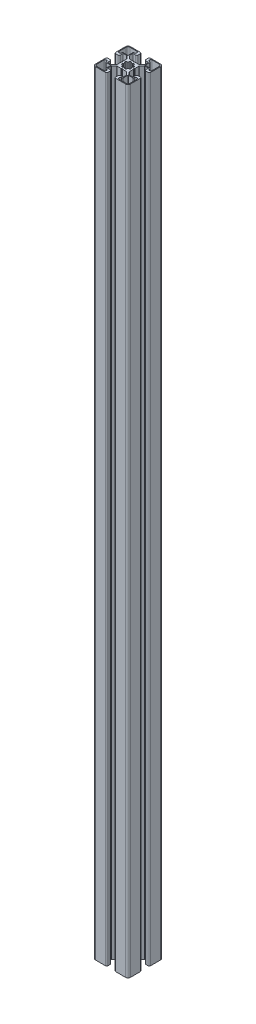
SolidWorks part; units mm, degrees
material "Commercially Pure CP-Ti UNS R50400 (SS)"
ref_plane "Front Plane" through (0, 0, 0) normal (0, 0, 1) x (1, 0, 0)
ref_plane "Top Plane" through (0, 0, 0) normal (0, 1, 0) x (1, 0, 0)
ref_plane "Right Plane" through (0, 0, 0) normal (1, 0, 0) x (0, 0, -1)
sketch "Sketch1" plane through (0, 0, 0) normal (0, 1, 0) x (1, 0, 0)
  line L0 (13.9698, 21.2743) -> (13.5298, 21.2743)
  line L1 (12.0298, 22.7743) -> (12.0298, 23.2743)
  line L2 (13.5298, 24.7743) -> (23.1398, 24.7743)
  line L3 (25.4198, 22.4943) -> (25.4198, 12.8843)
  line L4 (23.9198, 11.3843) -> (23.4198, 11.3843)
  line L5 (21.9198, 12.8843) -> (21.9198, 13.3243)
  line L6 (20.9198, 14.3243) -> (15.3498, 14.3243)
  line L7 (14.9698, 14.7043) -> (14.9698, 20.2743)
  line L8 (21.9589, -6.6897) -> (21.9589, -6.2497)
  line L9 (23.4589, -4.7497) -> (23.9589, -4.7497)
  line L10 (25.4589, -6.2497) -> (25.4589, -15.8597)
  line L11 (23.1789, -18.1397) -> (13.5689, -18.1397)
  line L12 (12.0689, -16.6397) -> (12.0689, -16.1397)
  line L13 (13.5689, -14.6397) -> (14.0089, -14.6397)
  line L14 (15.0089, -13.6397) -> (15.0089, -8.0697)
  line L15 (15.3889, -7.6897) -> (20.9589, -7.6897)
  line L16 (-6.0052, -14.6787) -> (-5.5652, -14.6787)
  line L17 (-4.0652, -16.1787) -> (-4.0652, -16.6787)
  line L18 (-5.5652, -18.1787) -> (-15.1752, -18.1787)
  line L19 (-17.4552, -15.8987) -> (-17.4552, -6.2887)
  line L20 (-15.9552, -4.7887) -> (-15.4552, -4.7887)
  line L21 (-13.9552, -6.2887) -> (-13.9552, -6.7287)
  line L22 (-12.9552, -7.7287) -> (-7.3852, -7.7287)
  line L23 (-7.0052, -8.1087) -> (-7.0052, -13.6787)
  line L24 (1.8289, -2.4886) -> (1.4132, -2.3164)
  line L25 (-1.632, 0.7289) -> (-1.8042, 1.1447)
  line L26 (-1.804, 5.4512) -> (-1.6318, 5.867)
  line L27 (1.4134, 8.9121) -> (1.8292, 9.0843)
  line L28 (6.1358, 9.0842) -> (6.5515, 8.912)
  line L29 (9.5966, 5.8667) -> (9.7688, 5.451)
  line L30 (9.7687, 1.1444) -> (9.5965, 0.7287)
  line L31 (6.5512, -2.3165) -> (6.1355, -2.4887)
  line L32 (-13.9942, 13.2853) -> (-13.9942, 12.8453)
  line L33 (-15.4942, 11.3453) -> (-15.9942, 11.3453)
  line L34 (-17.4942, 12.8453) -> (-17.4942, 22.4553)
  line L35 (-15.2142, 24.7353) -> (-5.6042, 24.7353)
  line L36 (-4.1042, 23.2353) -> (-4.1042, 22.7353)
  line L37 (-5.6042, 21.2353) -> (-6.0442, 21.2353)
  line L38 (-7.0442, 20.2353) -> (-7.0442, 14.6653)
  line L39 (-7.4242, 14.2853) -> (-12.9942, 14.2853)
  line L40 (4.9058, 11.2153) -> (4.0058, 10.7002)
  line L41 (4.0058, 10.7002) -> (3.1058, 11.2153)
  line L42 (3.1058, 11.2153) -> (-2.1975, 11.2153)
  line L43 (-2.4662, 11.3266) -> (-5.9329, 14.7933)
  line L44 (-6.0442, 15.062) -> (-6.0442, 19.3553)
  line L45 (-5.6642, 19.7353) -> (-2.5792, 19.7353)
  line L46 (-1.0592, 21.2553) -> (-1.0592, 24.2153)
  line L47 (-2.5792, 25.7353) -> (-15.4942, 25.7353)
  line L48 (-18.4942, 22.7353) -> (-18.4942, 9.8203)
  line L49 (-16.9742, 8.3003) -> (-14.0142, 8.3003)
  line L50 (-12.4942, 9.8203) -> (-12.4942, 12.9053)
  line L51 (-12.1142, 13.2853) -> (-7.8138, 13.2853)
  line L52 (-7.5451, 13.174) -> (-4.0855, 9.7144)
  line L53 (-3.9742, 9.4457) -> (-3.9742, 4.1353)
  line L54 (-3.9742, 4.1353) -> (-3.4546, 3.2353)
  line L55 (-3.4546, 3.2353) -> (-3.9742, 2.3353)
  line L56 (-3.9742, 2.3353) -> (-3.9742, -2.968)
  line L57 (-4.0855, -3.2367) -> (-7.5522, -6.7034)
  line L58 (-7.8209, -6.8147) -> (-12.1142, -6.8147)
  line L59 (-12.4942, -6.4347) -> (-12.4942, -3.3497)
  line L60 (-14.0142, -1.8297) -> (-16.9742, -1.8297)
  line L61 (-18.4942, -3.3497) -> (-18.4942, -16.2647)
  line L62 (-15.4942, -19.2647) -> (-2.5792, -19.2647)
  line L63 (-1.0592, -17.7447) -> (-1.0592, -14.7847)
  line L64 (-2.5792, -13.2647) -> (-5.6642, -13.2647)
  line L65 (-6.0442, -12.8847) -> (-6.0442, -8.5843)
  line L66 (-5.9329, -8.3156) -> (-2.4733, -4.856)
  line L67 (-2.2046, -4.7447) -> (3.1058, -4.7447)
  line L68 (3.1058, -4.7447) -> (4.0058, -4.2295)
  line L69 (4.0058, -4.2295) -> (4.9058, -4.7447)
  line L70 (4.9058, -4.7447) -> (10.2091, -4.7447)
  line L71 (10.4778, -4.856) -> (13.9445, -8.3227)
  line L72 (14.0558, -8.5914) -> (14.0558, -12.8847)
  line L73 (13.6758, -13.2647) -> (10.5908, -13.2647)
  line L74 (9.0708, -14.7847) -> (9.0708, -17.7447)
  line L75 (10.5908, -19.2647) -> (23.5058, -19.2647)
  line L76 (26.5058, -16.2647) -> (26.5058, -3.3497)
  line L77 (24.9858, -1.8297) -> (22.0258, -1.8297)
  line L78 (20.5058, -3.3497) -> (20.5058, -6.4347)
  line L79 (20.1258, -6.8147) -> (15.8254, -6.8147)
  line L80 (15.5567, -6.7034) -> (12.0971, -3.2438)
  line L81 (11.9858, -2.9751) -> (11.9858, 2.3353)
  line L82 (11.9858, 2.3353) -> (11.4662, 3.2353)
  line L83 (11.4662, 3.2353) -> (11.9858, 4.1353)
  line L84 (11.9858, 4.1353) -> (11.9858, 9.4386)
  line L85 (12.0971, 9.7073) -> (15.5638, 13.174)
  line L86 (15.8325, 13.2853) -> (20.1258, 13.2853)
  line L87 (20.5058, 12.9053) -> (20.5058, 9.8203)
  line L88 (22.0258, 8.3003) -> (24.9858, 8.3003)
  line L89 (26.5058, 9.8203) -> (26.5058, 22.7353)
  line L90 (23.5058, 25.7353) -> (10.5908, 25.7353)
  line L91 (9.0708, 24.2153) -> (9.0708, 21.2553)
  line L92 (10.5908, 19.7353) -> (13.6758, 19.7353)
  line L93 (14.0558, 19.3553) -> (14.0558, 15.0549)
  line L94 (13.9445, 14.7862) -> (10.4849, 11.3266)
  line L95 (10.2162, 11.2153) -> (4.9058, 11.2153)
  arc A0 (14.9698, 20.2743) -> (13.9698, 21.2743) centre (13.9698, 20.2743) ccw
  arc A1 (12.0298, 22.7743) -> (13.5298, 21.2743) centre (13.5298, 22.7743) ccw
  arc A2 (13.5298, 24.7743) -> (12.0298, 23.2743) centre (13.5298, 23.2743) ccw
  arc A3 (25.4198, 22.4943) -> (23.1398, 24.7743) centre (23.1398, 22.4943) ccw
  arc A4 (23.9198, 11.3843) -> (25.4198, 12.8843) centre (23.9198, 12.8843) ccw
  arc A5 (21.9198, 12.8843) -> (23.4198, 11.3843) centre (23.4198, 12.8843) ccw
  arc A6 (21.9198, 13.3243) -> (20.9198, 14.3243) centre (20.9198, 13.3243) ccw
  arc A7 (14.9698, 14.7043) -> (15.3498, 14.3243) centre (15.3498, 14.7043) ccw
  arc A8 (20.9589, -7.6897) -> (21.9589, -6.6897) centre (20.9589, -6.6897) ccw
  arc A9 (23.4589, -4.7497) -> (21.9589, -6.2497) centre (23.4589, -6.2497) ccw
  arc A10 (25.4589, -6.2497) -> (23.9589, -4.7497) centre (23.9589, -6.2497) ccw
  arc A11 (23.1789, -18.1397) -> (25.4589, -15.8597) centre (23.1789, -15.8597) ccw
  arc A12 (12.0689, -16.6397) -> (13.5689, -18.1397) centre (13.5689, -16.6397) ccw
  arc A13 (13.5689, -14.6397) -> (12.0689, -16.1397) centre (13.5689, -16.1397) ccw
  arc A14 (14.0089, -14.6397) -> (15.0089, -13.6397) centre (14.0089, -13.6397) ccw
  arc A15 (15.3889, -7.6897) -> (15.0089, -8.0697) centre (15.3889, -8.0697) ccw
  arc A16 (-7.0052, -13.6787) -> (-6.0052, -14.6787) centre (-6.0052, -13.6787) ccw
  arc A17 (-4.0652, -16.1787) -> (-5.5652, -14.6787) centre (-5.5652, -16.1787) ccw
  arc A18 (-5.5652, -18.1787) -> (-4.0652, -16.6787) centre (-5.5652, -16.6787) ccw
  arc A19 (-17.4552, -15.8987) -> (-15.1752, -18.1787) centre (-15.1752, -15.8987) ccw
  arc A20 (-15.9552, -4.7887) -> (-17.4552, -6.2887) centre (-15.9552, -6.2887) ccw
  arc A21 (-13.9552, -6.2887) -> (-15.4552, -4.7887) centre (-15.4552, -6.2887) ccw
  arc A22 (-13.9552, -6.7287) -> (-12.9552, -7.7287) centre (-12.9552, -6.7287) ccw
  arc A23 (-7.0052, -8.1087) -> (-7.3852, -7.7287) centre (-7.3852, -8.1087) ccw
  arc A24 (1.0363, -0.7421) -> (1.4132, -2.3164) centre (1.7959, -1.3925) ccw
  arc A25 (-0.0577, 0.352) -> (1.0363, -0.7421) centre (3.9823, 3.2978) ccw
  arc A26 (-1.632, 0.7289) -> (-0.0577, 0.352) centre (-0.7081, 1.1116) ccw
  arc A27 (-0.9575, 2.5244) -> (-1.8042, 1.1447) centre (-0.8803, 1.5274) ccw
  arc A28 (-0.9574, 4.0715) -> (-0.9575, 2.5244) centre (3.9823, 3.2978) ccw
  arc A29 (-1.804, 5.4512) -> (-0.9574, 4.0715) centre (-0.8802, 5.0686) ccw
  arc A30 (-0.0575, 6.2439) -> (-1.6318, 5.867) centre (-0.708, 5.4843) ccw
  arc A31 (1.0365, 7.3379) -> (-0.0575, 6.2439) centre (3.9823, 3.2978) ccw
  arc A32 (1.4134, 8.9121) -> (1.0365, 7.3379) centre (1.7961, 7.9882) ccw
  arc A33 (3.2089, 8.2376) -> (1.8292, 9.0843) centre (2.2119, 8.1604) ccw
  arc A34 (4.7561, 8.2376) -> (3.2089, 8.2376) centre (3.9823, 3.2978) ccw
  arc A35 (6.1358, 9.0842) -> (4.7561, 8.2376) centre (5.7531, 8.1603) ccw
  arc A36 (6.9284, 7.3377) -> (6.5515, 8.912) centre (6.1688, 7.9881) ccw
  arc A37 (8.0224, 6.2437) -> (6.9284, 7.3377) centre (3.9823, 3.2978) ccw
  arc A38 (9.5966, 5.8667) -> (8.0224, 6.2437) centre (8.6727, 5.484) ccw
  arc A39 (8.9222, 4.0713) -> (9.7688, 5.451) centre (8.845, 5.0683) ccw
  arc A40 (8.9221, 2.5241) -> (8.9222, 4.0713) centre (3.9823, 3.2978) ccw
  arc A41 (9.7687, 1.1444) -> (8.9221, 2.5241) centre (8.8448, 1.5271) ccw
  arc A42 (8.0222, 0.3518) -> (9.5965, 0.7287) centre (8.6726, 1.1113) ccw
  arc A43 (6.9282, -0.7422) -> (8.0222, 0.3518) centre (3.9823, 3.2978) ccw
  arc A44 (6.5512, -2.3165) -> (6.9282, -0.7422) centre (6.1685, -1.3926) ccw
  arc A45 (4.7558, -1.642) -> (6.1355, -2.4887) centre (5.7528, -1.5648) ccw
  arc A46 (3.2086, -1.642) -> (4.7558, -1.642) centre (3.9823, 3.2978) ccw
  arc A47 (1.8289, -2.4886) -> (3.2086, -1.642) centre (2.2116, -1.5647) ccw
  arc A48 (-12.9942, 14.2853) -> (-13.9942, 13.2853) centre (-12.9942, 13.2853) ccw
  arc A49 (-15.4942, 11.3453) -> (-13.9942, 12.8453) centre (-15.4942, 12.8453) ccw
  arc A50 (-17.4942, 12.8453) -> (-15.9942, 11.3453) centre (-15.9942, 12.8453) ccw
  arc A51 (-15.2142, 24.7353) -> (-17.4942, 22.4553) centre (-15.2142, 22.4553) ccw
  arc A52 (-4.1042, 23.2353) -> (-5.6042, 24.7353) centre (-5.6042, 23.2353) ccw
  arc A53 (-5.6042, 21.2353) -> (-4.1042, 22.7353) centre (-5.6042, 22.7353) ccw
  arc A54 (-6.0442, 21.2353) -> (-7.0442, 20.2353) centre (-6.0442, 20.2353) ccw
  arc A55 (-7.4242, 14.2853) -> (-7.0442, 14.6653) centre (-7.4242, 14.6653) ccw
  arc A56 (-2.4662, 11.3266) -> (-2.1975, 11.2153) centre (-2.1975, 11.5953) ccw
  arc A57 (-6.0442, 15.062) -> (-5.9329, 14.7933) centre (-5.6642, 15.062) ccw
  arc A58 (-5.6642, 19.7353) -> (-6.0442, 19.3553) centre (-5.6642, 19.3553) ccw
  arc A59 (-2.5792, 19.7353) -> (-1.0592, 21.2553) centre (-2.5792, 21.2553) ccw
  arc A60 (-1.0592, 24.2153) -> (-2.5792, 25.7353) centre (-2.5792, 24.2153) ccw
  arc A61 (-15.4942, 25.7353) -> (-18.4942, 22.7353) centre (-15.4942, 22.7353) ccw
  arc A62 (-18.4942, 9.8203) -> (-16.9742, 8.3003) centre (-16.9742, 9.8203) ccw
  arc A63 (-14.0142, 8.3003) -> (-12.4942, 9.8203) centre (-14.0142, 9.8203) ccw
  arc A64 (-12.1142, 13.2853) -> (-12.4942, 12.9053) centre (-12.1142, 12.9053) ccw
  arc A65 (-7.5451, 13.174) -> (-7.8138, 13.2853) centre (-7.8138, 12.9053) ccw
  arc A66 (-3.9742, 9.4457) -> (-4.0855, 9.7144) centre (-4.3542, 9.4457) ccw
  arc A67 (-4.0855, -3.2367) -> (-3.9742, -2.968) centre (-4.3542, -2.968) ccw
  arc A68 (-7.8209, -6.8147) -> (-7.5522, -6.7034) centre (-7.8209, -6.4347) ccw
  arc A69 (-12.4942, -6.4347) -> (-12.1142, -6.8147) centre (-12.1142, -6.4347) ccw
  arc A70 (-12.4942, -3.3497) -> (-14.0142, -1.8297) centre (-14.0142, -3.3497) ccw
  arc A71 (-16.9742, -1.8297) -> (-18.4942, -3.3497) centre (-16.9742, -3.3497) ccw
  arc A72 (-18.4942, -16.2647) -> (-15.4942, -19.2647) centre (-15.4942, -16.2647) ccw
  arc A73 (-2.5792, -19.2647) -> (-1.0592, -17.7447) centre (-2.5792, -17.7447) ccw
  arc A74 (-1.0592, -14.7847) -> (-2.5792, -13.2647) centre (-2.5792, -14.7847) ccw
  arc A75 (-6.0442, -12.8847) -> (-5.6642, -13.2647) centre (-5.6642, -12.8847) ccw
  arc A76 (-5.9329, -8.3156) -> (-6.0442, -8.5843) centre (-5.6642, -8.5843) ccw
  arc A77 (-2.2046, -4.7447) -> (-2.4733, -4.856) centre (-2.2046, -5.1247) ccw
  arc A78 (10.4778, -4.856) -> (10.2091, -4.7447) centre (10.2091, -5.1247) ccw
  arc A79 (14.0558, -8.5914) -> (13.9445, -8.3227) centre (13.6758, -8.5914) ccw
  arc A80 (13.6758, -13.2647) -> (14.0558, -12.8847) centre (13.6758, -12.8847) ccw
  arc A81 (10.5908, -13.2647) -> (9.0708, -14.7847) centre (10.5908, -14.7847) ccw
  arc A82 (9.0708, -17.7447) -> (10.5908, -19.2647) centre (10.5908, -17.7447) ccw
  arc A83 (23.5058, -19.2647) -> (26.5058, -16.2647) centre (23.5058, -16.2647) ccw
  arc A84 (26.5058, -3.3497) -> (24.9858, -1.8297) centre (24.9858, -3.3497) ccw
  arc A85 (22.0258, -1.8297) -> (20.5058, -3.3497) centre (22.0258, -3.3497) ccw
  arc A86 (20.1258, -6.8147) -> (20.5058, -6.4347) centre (20.1258, -6.4347) ccw
  arc A87 (15.5567, -6.7034) -> (15.8254, -6.8147) centre (15.8254, -6.4347) ccw
  arc A88 (11.9858, -2.9751) -> (12.0971, -3.2438) centre (12.3658, -2.9751) ccw
  arc A89 (12.0971, 9.7073) -> (11.9858, 9.4386) centre (12.3658, 9.4386) ccw
  arc A90 (15.8325, 13.2853) -> (15.5638, 13.174) centre (15.8325, 12.9053) ccw
  arc A91 (20.5058, 12.9053) -> (20.1258, 13.2853) centre (20.1258, 12.9053) ccw
  arc A92 (20.5058, 9.8203) -> (22.0258, 8.3003) centre (22.0258, 9.8203) ccw
  arc A93 (24.9858, 8.3003) -> (26.5058, 9.8203) centre (24.9858, 9.8203) ccw
  arc A94 (26.5058, 22.7353) -> (23.5058, 25.7353) centre (23.5058, 22.7353) ccw
  arc A95 (10.5908, 25.7353) -> (9.0708, 24.2153) centre (10.5908, 24.2153) ccw
  arc A96 (9.0708, 21.2553) -> (10.5908, 19.7353) centre (10.5908, 21.2553) ccw
  arc A97 (14.0558, 19.3553) -> (13.6758, 19.7353) centre (13.6758, 19.3553) ccw
  arc A98 (13.9445, 14.7862) -> (14.0558, 15.0549) centre (13.6758, 15.0549) ccw
  arc A99 (10.2162, 11.2153) -> (10.4849, 11.3266) centre (10.2162, 11.5953) ccw
extrude "Extrude1" add sketch "Sketch1" along normal blind 1000
